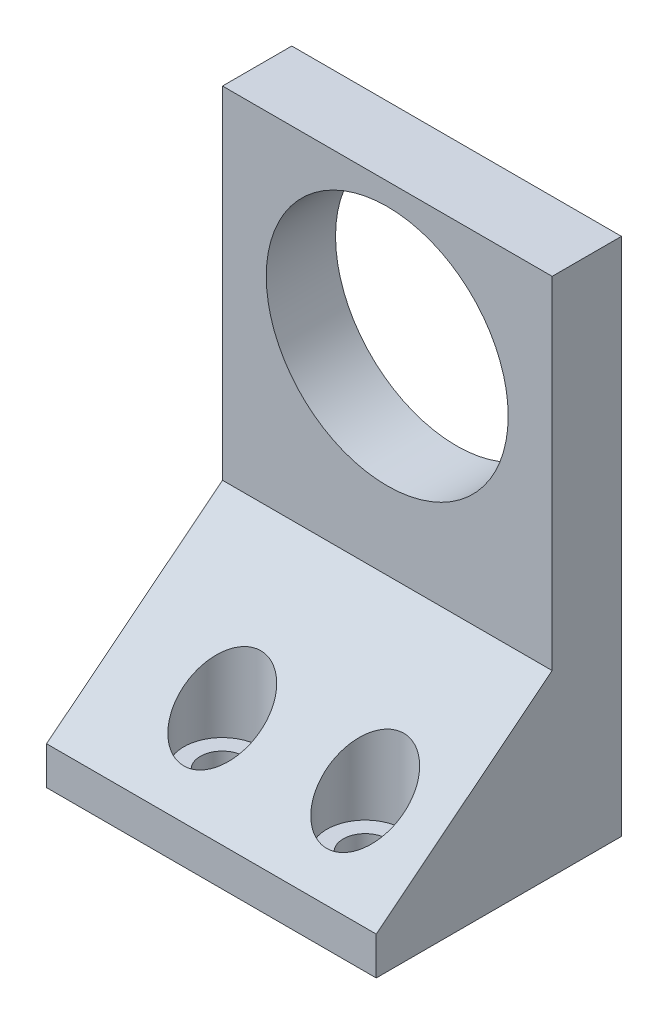
SolidWorks part; units mm, degrees
material "ABS"
ref_plane "Front Plane" through (0, 0, 0) normal (0, 0, 1) x (1, 0, 0)
ref_plane "Top Plane" through (0, 0, 0) normal (0, 1, 0) x (1, 0, 0)
ref_plane "Right Plane" through (0, 0, 0) normal (1, 0, 0) x (0, 0, -1)
sketch "Sketch1" plane through (0, 0, 0) normal (0, 0, 1) x (1, 0, 0)
  line L1 (-76.1871, 64.9281) -> (16.8129, 64.9281)
  line L2 (-76.1871, 64.9281) -> (-76.1871, -35.0719)
  line L3 (-76.1871, -35.0719) -> (16.8129, -35.0719)
  line L4 (16.8129, 64.9281) -> (16.8129, -35.0719)
  dimension "D1" = 93
  dimension "D2" = 100
extrude "Boss-Extrude2" add sketch "Sketch1" along normal blind 10 contours L1 L4 L3 L2
sketch "Sketch3" plane through (0, 0, 0) normal (0, 0, -1) x (-1, 0, 0)
  line L0 (76.1871, -35.0719) -> (-16.8129, -35.0719) construction
  line L1 (-16.8129, 64.9281) -> (-6.8129, 64.9281)
  line L2 (-16.8129, 64.9281) -> (-16.8129, -35.0719)
  line L3 (-16.8129, -35.0719) -> (-6.8129, -35.0719)
  line L4 (-6.8129, 64.9281) -> (-6.8129, -35.0719)
  line L5 (-16.8129, 64.9281) -> (-16.8129, -35.0719) construction
  dimension "D1" = 0
  dimension "D2" = 0
  dimension "D3" = 10
  dimension "D4" = 100
sketch "Sketch4" plane through (16.8129, 0, 0) normal (1, 0, 0) x (0, 0, -1)
  line L0 (-10, 64.9281) -> (-10, -35.0719) construction
  line L1 (-10, -5.0719) -> (0.01, -5.0719)
  line L2 (-10, -5.0719) -> (-10, -20.0719)
  line L3 (-10, -20.0719) -> (0.01, -20.0719)
  line L4 (0.01, -5.0719) -> (0.01, -20.0719)
  line L6 (-10, -35.0719) -> (0, -35.0719) construction
  dimension "D1" = 15
  dimension "D2" = 15
extrude "Boss-Extrude4" add sketch "Sketch4" along normal blind 24
sketch "Sketch5" plane through (0, -5.0719, 0) normal (0, 1, 0) x (1, 0, 0)
  line L0 (40.8129, -10) -> (16.8129, -10) construction
  line L2 (16.8129, 0) -> (16.8129, -10) construction
  circle A0 centre (26.8129, -5) radius 2
  dimension "D2" = 4
  dimension "D3" = 10
  dimension "D1" = 5
extrude "Cut-Extrude1" cut sketch "Sketch5" against normal blind 50
sketch "Sketch6" plane through (0, 0, 10) normal (0, 0, -1) x (-1, 0, 0)
  line L2 (76.1871, -35.0719) -> (-16.8129, -35.0719) construction
  line L3 (-16.8129, 64.9281) -> (-16.8129, -35.0719) construction
  circle A0 centre (-1.8129, -24.5719) radius 7.5
  dimension "D1" = 15
  dimension "D2" = 10.5
  dimension "D3" = 15
sketch "Sketch7" plane through (0, 0, 0) normal (0, 0, -1) x (-1, 0, 0)
  circle A0 centre (24.1871, 36.9281) radius 11
  circle A1 centre (24.1871, 36.9281) radius 9.3 construction
  dimension "D1" = 22
extrude "Cut-Extrude3" cut sketch "Sketch7" against normal blind 50
sketch "Sketch14" plane through (0, 0, 10) normal (0, 0, 1) x (1, 0, 0)
  line L0 (16.8129, 64.9281) -> (16.8129, -5.0719) construction
  line L1 (-44.6871, 15.7891) -> (16.8129, 15.7891)
  line L2 (-44.6871, 15.7891) -> (-44.6871, 57.7891)
  line L3 (-44.6871, 57.7891) -> (16.8129, 57.7891)
  line L4 (16.8129, 15.7891) -> (16.8129, 57.7891)
  dimension "D1" = 42
  dimension "D3" = 61.5
extrude "Cut-Extrude8" cut sketch "Sketch14" against normal blind 4
sketch "Sketch15" plane through (0, 0, 0) normal (0, 0, -1) x (-1, 0, 0)
  circle A0 centre (24.1871, 36.9281) radius 10
  circle A1 centre (24.1871, 36.9281) radius 11 construction
  dimension "D1" = 20
  dimension "D2" = 0
sketch "Sketch16" plane through (0, 0, 10) normal (0, 0, 1) x (1, 0, 0)
  line L0 (-43.6871, 56.9281) -> (14.3129, 56.9281) construction
  line L1 (-44.1871, 57.3281) -> (16.8129, 57.3281)
  line L2 (-44.1871, 57.3281) -> (-44.1871, 64.9281)
  line L3 (-44.1871, 64.9281) -> (16.8129, 64.9281)
  line L4 (16.8129, 57.3281) -> (16.8129, 64.9281)
  dimension "D1" = 0.4
sketch "Sketch17" plane through (0, 0, 10) normal (0, 0, 1) x (1, 0, 0)
  line L0 (16.8129, 15.7891) -> (16.8129, -5.0719) construction
  line L1 (-44.1871, 16.7281) -> (16.8129, 16.7281)
  line L2 (-44.1871, 16.7281) -> (-44.1871, -20.0719)
  line L3 (-44.1871, -20.0719) -> (16.8129, -20.0719)
  line L4 (16.8129, 16.7281) -> (16.8129, -20.0719)
  line L5 (-43.6871, 16.9281) -> (14.3129, 16.9281) construction
  line L6 (40.8129, -20.0719) -> (16.8129, -20.0719) construction
  line L9 (16.8129, -20.0719) -> (40.8129, -20.0719)
  line L10 (16.8129, -20.0719) -> (16.8129, -5.0719)
  line L11 (16.8129, -5.0719) -> (40.8129, -5.0719)
  line L12 (40.8129, -20.0719) -> (40.8129, -5.0719)
  line L13 (16.8129, -20.0719) -> (40.8129, -5.0719) construction
  line L14 (16.8129, -5.0719) -> (40.8129, -20.0719) construction
  point P16 (28.8129, -12.5719)
  dimension "D1" = 0.2
  dimension "D2" = 0
sketch "Sketch19" plane through (0, 0, 0) normal (0, 0, -1) x (-1, 0, 0)
  line L1 (-16.8129, 64.9281) -> (-16.8129, -35.0719) construction
  circle A0 centre (53.1871, 36.9281) radius 11
  circle A1 centre (24.1871, 36.9281) radius 10 construction
  dimension "D1" = 22
  dimension "D3" = 0
  dimension "D2" = 70
extrude "Cut-Extrude11" cut sketch "Sketch19" against normal blind 15
sketch "Sketch20" plane through (0, 0, 6) normal (0, 0, 1) x (1, 0, 0)
  circle A0 centre (-34.6871, 50.9281) radius 2
  circle A1 centre (5.3129, 50.9281) radius 2
  circle A2 centre (-34.6871, 22.9281) radius 2
  circle A3 centre (5.3129, 22.9281) radius 2
  arc A5 (-27.0471, 34.1316) -> (-27.0471, 39.7246) centre (-24.1871, 36.9281) ccw construction
  circle A6 centre (-24.1871, 36.9281) radius 11 construction
  dimension "D1" = 4
  dimension "D2" = 4
  dimension "D3" = 4
  dimension "D4" = 4
  dimension "D5" = 0
  dimension "D6" = 28
  dimension "D7" = 0
  dimension "D8" = 40
  dimension "D9" = 14
  dimension "D10" = 10.5
  dimension "D11" = 28
  dimension "D12" = 40
extrude "Cut-Extrude12" cut sketch "Sketch20" against normal blind 10
sketch "Sketch8" plane through (0, 64.9281, 0) normal (0, 1, 0) x (1, 0, 0)
  line L0 (-76.1871, -10) -> (16.8129, -10) construction
  line L5 (16.8129, 0) -> (12.3014, -10) construction
  line L6 (16.8129, -10) -> (7.8859, 0) construction
  line L8 (16.8129, -10) -> (16.8129, 0) construction
  line L9 (-76.1871, 0) -> (16.8129, 0) construction
  circle A0 centre (11.8129, -7) radius 1.4
  circle A1 centre (-13.1871, -7) radius 1.4
  point P4 (13.816, -6.6429)
  dimension "D1" = 25
  dimension "D2" = 5
  dimension "D3" = 2.8
  dimension "D4" = 7
  dimension "D5" = 7
sketch "Sketch21" plane through (0, 0, 0) normal (0, 0, -1) x (-1, 0, 0)
  line L1 (76.1871, 64.9281) -> (36.1871, 64.9281)
  line L2 (76.1871, 64.9281) -> (76.1871, 58.9281)
  line L3 (76.1871, 58.9281) -> (36.1871, 58.9281)
  line L4 (36.1871, 64.9281) -> (36.1871, 58.9281)
  dimension "D1" = 6
  dimension "D2" = 40
extrude "Boss-Extrude5" add sketch "Sketch21" along normal blind 27
sketch "Sketch22" plane through (0, 58.9281, 0) normal (0, -1, 0) x (1, 0, 0)
  line L0 (-76.1871, -27) -> (-76.1871, 0) construction
  line L1 (-36.1871, -27) -> (-76.1871, -27)
  line L2 (-36.1871, -27) -> (-36.1871, -20.7)
  line L3 (-36.1871, -20.7) -> (-76.1871, -20.7)
  line L4 (-76.1871, -27) -> (-76.1871, -20.7)
  dimension "D1" = 6.3
extrude "Boss-Extrude7" add sketch "Sketch22" along normal blind 40
sketch "Sketch23" plane through (0, 0, 10) normal (0, 0, 1) x (1, 0, 0)
  circle A0 centre (-53.1871, 36.9281) radius 8
  arc A1 (-44.6871, 43.9102) -> (-44.6871, 29.9459) centre (-53.1871, 36.9281) ccw construction
  dimension "D1" = 16
  dimension "D2" = 0
extrude "Cut-Extrude13" cut sketch "Sketch23" against normal blind 40
sketch "Sketch24" plane through (0, 0, 10) normal (0, 0, 1) x (1, 0, 0)
  line L1 (-76.1871, -35.0719) -> (42.0908, -35.0719)
  line L2 (-76.1871, -35.0719) -> (-76.1871, 6.7281)
  line L3 (-76.1871, 6.7281) -> (42.0908, 6.7281)
  line L4 (42.0908, -35.0719) -> (42.0908, 6.7281)
  dimension "D1" = 41.8
extrude "Cut-Extrude14" cut sketch "Sketch24" against normal blind 40
sketch "Sketch25" plane through (0, 0, 10) normal (0, 0, 1) x (1, 0, 0)
  line L5 (-44.6871, 29.9459) -> (-44.6871, 15.7891) construction
  line L6 (-76.1871, 6.7281) -> (-44.6871, 6.7281)
  line L7 (-76.1871, 6.7281) -> (-76.1871, 29.9281)
  line L8 (-76.1871, 29.9281) -> (-44.6871, 29.9281)
  line L9 (-44.6871, 6.7281) -> (-44.6871, 29.9281)
  arc A2 (-44.6871, 43.9102) -> (-44.6871, 29.9459) centre (-53.1871, 36.9281) ccw construction
  dimension "D1" = 7
extrude "Cut-Extrude15" cut sketch "Sketch25" against normal blind 20
sketch "Sketch26" plane through (0, 0, 6) normal (0, 0, 1) x (1, 0, 0)
  line L1 (-44.6871, 15.7891) -> (-36.2375, 15.7891)
  line L2 (-44.6871, 15.7891) -> (-44.6871, 21.6647)
  line L3 (-44.6871, 21.6647) -> (-36.2375, 21.6647)
  line L4 (-36.2375, 15.7891) -> (-36.2375, 21.6647)
  line L5 (-44.6871, 57.7891) -> (-36.2375, 57.7891)
  line L6 (-44.6871, 57.7891) -> (-44.6871, 52.1914)
  line L7 (-44.6871, 52.1914) -> (-36.2375, 52.1914)
  line L8 (-36.2375, 57.7891) -> (-36.2375, 52.1914)
  line L9 (6.8634, 52.1914) -> (14.3021, 52.1914)
  line L10 (6.8634, 52.1914) -> (6.8634, 57.7891)
  line L11 (6.8634, 57.7891) -> (14.3021, 57.7891)
  line L12 (14.3021, 52.1914) -> (14.3021, 57.7891)
  line L13 (6.8634, 20.9281) -> (14.3021, 20.9281)
  line L14 (6.8634, 20.9281) -> (6.8634, 15.7891)
  line L15 (6.8634, 15.7891) -> (14.3021, 15.7891)
  line L16 (14.3021, 20.9281) -> (14.3021, 15.7891)
  circle A0 centre (-34.6871, 22.9281) radius 2 construction
  circle A1 centre (-34.6871, 50.9281) radius 2 construction
  circle A2 centre (5.3129, 50.9281) radius 2 construction
  circle A3 centre (5.3129, 22.9281) radius 4
  circle A4 centre (5.3129, 50.9281) radius 4
  circle A5 centre (-34.6871, 50.9281) radius 4
  circle A6 centre (-34.6871, 22.9281) radius 4
  circle A7 centre (5.3129, 50.9281) radius 4
  circle A8 centre (5.3129, 22.9281) radius 4
  circle A9 centre (-34.6871, 50.9281) radius 4
  circle A10 centre (-34.6871, 22.9281) radius 4
  line M5 (-44.6871, 57.7891) -> (-44.6871, 43.9102)
  line M8 (-44.6871, 29.9281) -> (-44.6871, 15.7891)
  line M9 (-44.6871, 15.7891) -> (16.8129, 15.7891)
  line M11 (16.8129, 57.7891) -> (-44.6871, 57.7891)
  dimension "D1" = 8
  dimension "D2" = 8
  dimension "D3" = 8
  dimension "D4" = 8
extrude "Cut-Extrude18" cut sketch "Sketch26" against normal blind 3 contours A4 L9 L12 L10 M11 | A3 L14 L16 L13 M9 | A5 L8 L7 M11 M5 | A6 L3 L4 M8 M9
sketch "Sketch27" plane through (0, 0, 6) normal (0, 0, 1) x (1, 0, 0)
  circle A0 centre (5.3129, 50.9281) radius 4.1
  circle A1 centre (5.3129, 22.9281) radius 4
  circle A2 centre (-34.6871, 50.9281) radius 4.1
  circle A3 centre (-34.6871, 22.9281) radius 4.1
  dimension "D1" = 8.2
  dimension "D2" = 8.2
  dimension "D3" = 8
  dimension "D4" = 8.2
extrude "Cut-Extrude29" cut sketch "Sketch27" against normal blind 3
sketch "Sketch28" plane through (0, 0, 0) normal (0, 0, -1) x (-1, 0, 0)
  line L5 (-16.8129, 6.7281) -> (44.6871, 6.7281) construction
  line L6 (-16.8129, 64.9281) -> (12.6871, 64.9281)
  line L7 (-16.8129, 64.9281) -> (-16.8129, 6.7281)
  line L8 (-16.8129, 6.7281) -> (12.6871, 6.7281)
  line L9 (12.6871, 64.9281) -> (12.6871, 6.7281)
  circle A1 centre (34.6871, 22.9281) radius 2 construction
  dimension "D1" = 22
extrude "Cut-Extrude30" cut sketch "Sketch28" against normal blind 23
sketch "Sketch29" plane through (0, 15.7891, 0) normal (0, 1, 0) x (1, 0, 0)
  line L1 (-44.6871, -10) -> (-12.6871, -10)
  line L2 (-44.6871, -10) -> (-44.6871, -6)
  line L3 (-44.6871, -6) -> (-12.6871, -6)
  line L4 (-12.6871, -10) -> (-12.6871, -6)
extrude "Cut-Extrude31" cut sketch "Sketch29" against normal blind 23
sketch "Sketch31" plane through (0, 6.7281, 0) normal (0, -1, 0) x (1, 0, 0)
  line L1 (-44.6871, 6) -> (-12.6871, 6)
  line L2 (-44.6871, 6) -> (-44.6871, 0)
  line L3 (-44.6871, 0) -> (-12.6871, 0)
  line L4 (-12.6871, 6) -> (-12.6871, 0)
extrude "Boss-Extrude9" add sketch "Sketch31" along normal blind 6.6
sketch "Sketch32" plane through (0, 0, 6) normal (0, 0, 1) x (1, 0, 0)
  line L0 (-12.6871, 0.1281) -> (-12.6871, 57.7891) construction
  line L1 (-44.6871, 0.1281) -> (-12.6871, 0.1281)
  line L2 (-44.6871, 0.1281) -> (-44.6871, 6.1281)
  line L3 (-44.6871, 6.1281) -> (-12.6871, 6.1281)
  line L4 (-12.6871, 0.1281) -> (-12.6871, 6.1281)
  dimension "D1" = 6
extrude "Boss-Extrude10" add sketch "Sketch32" along normal blind 10
sketch "Sketch33" plane through (0, 6.1281, 0) normal (0, 1, 0) x (1, 0, 0)
  line L0 (-12.6871, -16) -> (-44.6871, -16) construction
  line L1 (-44.6871, -16) -> (-44.6871, -6) construction
  line L2 (-12.6871, -16) -> (-12.6871, -6) construction
  circle A0 centre (-37.6871, -11) radius 2
  circle A1 centre (-19.6871, -11) radius 2
  point P8 (-44.6871, -11)
  dimension "D1" = 4
  dimension "D2" = 4
  dimension "D3" = 0
  dimension "D4" = 5
  dimension "D5" = 7
  dimension "D6" = 7
extrude "Cut-Extrude32" cut sketch "Sketch33" against normal blind 10
sketch "Sketch34" plane through (-12.6871, 0, 0) normal (1, 0, 0) x (0, 0, -1)
  line L0 (-16, 6.1281) -> (-6, 6.1281)
  line L1 (-6, 6.1281) -> (-6, 14.0584)
  line L2 (-6, 6.1281) -> (-6, 57.7891) construction
  line L3 (-6, 14.0584) -> (-16, 6.1281)
extrude "Boss-Extrude11" add sketch "Sketch34" against normal up to vertex
sketch "Sketch35" plane through (0, 6.1281, 0) normal (0, -1, 0) x (1, 0, 0)
  circle A0 centre (-19.6871, 11) radius 3.5
  circle A1 centre (-37.6871, 11) radius 3.5
  dimension "D1" = 7
  dimension "D2" = 7
extrude "Cut-Extrude33" cut sketch "Sketch35" against normal blind 10
sketch "Sketch36" plane through (0, 18.9281, 0) normal (0, -1, 0) x (1, 0, 0)
  line L1 (-76.1871, -20.7) -> (-36.1871, -20.7)
  line L2 (-76.1871, -20.7) -> (-76.1871, -27)
  line L3 (-76.1871, -27) -> (-36.1871, -27)
  line L4 (-36.1871, -20.7) -> (-36.1871, -27)
extrude "Boss-Extrude12" add sketch "Sketch36" along normal up to vertex (18.8 mm away)
sketch "Sketch37" plane through (0, 0, -20.7) normal (0, 0, 1) x (1, 0, 0)
  line L0 (-76.1871, 0.1281) -> (-76.1871, 58.9281) construction
  line L1 (-36.1871, 0.1281) -> (-76.1871, 0.1281)
  line L2 (-36.1871, 0.1281) -> (-36.1871, 6.1281)
  line L3 (-36.1871, 6.1281) -> (-76.1871, 6.1281)
  line L4 (-76.1871, 0.1281) -> (-76.1871, 6.1281)
  dimension "D1" = 6
extrude "Boss-Extrude13" add sketch "Sketch37" along normal blind 16
sketch "Sketch38" plane through (0, 6.1281, 0) normal (0, 1, 0) x (1, 0, 0)
  line L0 (-36.1871, 4.7) -> (-76.1871, 4.7) construction
  line L2 (-36.1871, 4.7) -> (-36.1871, 20.7) construction
  circle A0 centre (-58.1871, 10.7) radius 2
  circle A1 centre (-45.1871, 10.7) radius 2
  dimension "D1" = 4
  dimension "D2" = 4
  dimension "D3" = 6
  dimension "D4" = 13
  dimension "D5" = 9
  dimension "D6" = 6
extrude "Cut-Extrude34" cut sketch "Sketch38" against normal blind 16
sketch "Sketch39" plane through (-36.1871, 0, 0) normal (1, 0, 0) x (0, 0, -1)
  line L0 (4.7, 6.1281) -> (20.7, 18.8781)
  line L1 (20.7, 6.1281) -> (20.7, 58.9281) construction
  line L2 (20.7, 18.8781) -> (20.7, 6.1281)
  line L3 (20.7, 6.1281) -> (4.7, 6.1281)
extrude "Boss-Extrude14" add sketch "Sketch39" against normal up to vertex (40 mm away)
sketch "Sketch40" plane through (0, 6.1281, 0) normal (0, -1, 0) x (1, 0, 0)
  circle A0 centre (-45.1871, -10.7) radius 3.5
  circle A1 centre (-58.1871, -10.7) radius 3.5
  dimension "D1" = 7
  dimension "D2" = 7
extrude "Cut-Extrude35" cut sketch "Sketch40" against normal blind 16
sketch "Sketch41" plane through (-12.6871, 0, 0) normal (1, 0, 0) x (0, 0, -1)
  line L1 (0, 64.9281) -> (-16, 64.9281)
  line L2 (0, 64.9281) -> (0, 0.1281)
  line L3 (0, 0.1281) -> (-16, 0.1281)
  line L4 (-16, 64.9281) -> (-16, 0.1281)
extrude "Cut-Extrude36" cut sketch "Sketch41" against normal blind 76
sketch "Sketch42" plane through (-36.1871, 0, 0) normal (1, 0, 0) x (0, 0, -1)
  line L0 (27, 64.9281) -> (0, 64.9281) construction
  line L1 (20.7, 58.9281) -> (0, 58.9281)
  line L2 (20.7, 58.9281) -> (20.7, 64.9281)
  line L3 (20.7, 64.9281) -> (0, 64.9281)
  line L4 (0, 58.9281) -> (0, 64.9281)
extrude "Cut-Extrude37" cut sketch "Sketch42" against normal blind 76
sketch "Sketch43" plane through (0, 0, -4.7) normal (0, 0, 1) x (1, 0, 0)
  line L1 (-76.1871, 0.1281) -> (-65.8661, 0.1281)
  line L2 (-76.1871, 0.1281) -> (-76.1871, 73.2032)
  line L3 (-76.1871, 73.2032) -> (-65.8661, 73.2032)
  line L4 (-65.8661, 0.1281) -> (-65.8661, 73.2032)
extrude "Cut-Extrude38" cut sketch "Sketch43" against normal blind 30
sketch "Sketch44" plane through (0, 0, -4.7) normal (0, 0, 1) x (1, 0, 0)
  line L1 (-36.1871, 0.1281) -> (-38.1871, 0.1281)
  line L2 (-36.1871, 0.1281) -> (-36.1871, 70.9113)
  line L3 (-36.1871, 70.9113) -> (-38.1871, 70.9113)
  line L4 (-38.1871, 0.1281) -> (-38.1871, 70.9113)
  dimension "D1" = 2
extrude "Cut-Extrude39" cut sketch "Sketch44" against normal blind 30
sketch "Sketch45" plane through (0, 0, -20.7) normal (0, 0, 1) x (1, 0, 0)
  line L0 (-65.8661, 64.9281) -> (-65.8661, 18.8781) construction
  line L1 (-38.1871, 64.9281) -> (-65.8661, 64.9281)
  line L2 (-38.1871, 64.9281) -> (-38.1871, 49.9281)
  line L3 (-38.1871, 49.9281) -> (-65.8661, 49.9281)
  line L4 (-65.8661, 64.9281) -> (-65.8661, 49.9281)
  circle A0 centre (-53.1871, 36.9281) radius 8 construction
  dimension "D1" = 13
extrude "Cut-Extrude40" cut sketch "Sketch45" against normal blind 30
sketch "Sketch46" plane through (0, 0, -4.7) normal (0, 0, 1) x (1, 0, 0)
  line L0 (-38.1871, 6.1281) -> (-38.1871, 0.1281) construction
  line L1 (-65.8661, 0.1281) -> (-38.1871, 0.1281)
  line L2 (-65.8661, 0.1281) -> (-65.8661, 2.6681)
  line L3 (-65.8661, 2.6681) -> (-38.1871, 2.6681)
  line L4 (-38.1871, 0.1281) -> (-38.1871, 2.6681)
  dimension "D1" = 2.54
extrude "Cut-Extrude41" cut sketch "Sketch46" against normal blind 110
sketch "Sketch47" plane through (0, 0, -20.7) normal (0, 0, 1) x (1, 0, 0)
  circle A0 centre (-53.1871, 36.9281) radius 11
  circle A1 centre (-53.1871, 36.9281) radius 8 construction
  dimension "D1" = 0
  dimension "D2" = 22
extrude "Cut-Extrude42" cut sketch "Sketch47" against normal blind 20
sketch "Sketch48" plane through (-65.8661, 0, 0) normal (-1, 0, 0) x (0, 0, 1)
  line L0 (-27, 49.9281) -> (-20.7, 49.9281)
  line L1 (-20.7, 49.9281) -> (-20.7, 18.8781)
  line L2 (-20.7, 18.8781) -> (-4.7, 6.1281)
  line L3 (-4.7, 6.1281) -> (-4.7, 2.6681)
  line L4 (-4.7, 2.6681) -> (-27, 2.6681)
  line L5 (-27, 2.6681) -> (-27, 49.9281)
  line L6 (-20.7, 25.9281) -> (-20.7, 47.9281) construction
extrude "Boss-Extrude16" add sketch "Sketch48" along normal blind 2.3
